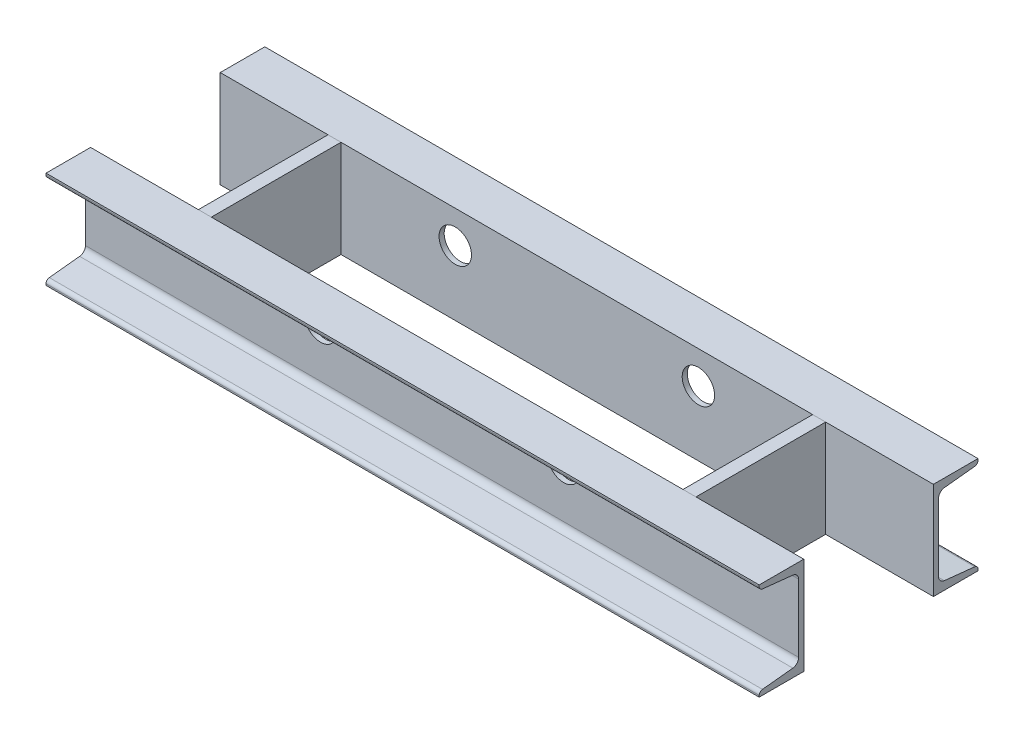
SolidWorks part; units mm, degrees
other "DetailItem17"
other "DetailItem18"
other "DetailItem14"
other "DetailItem15"
other "DetailItem16"
other "DetailItem19"
other "DetailItem20"
other "DetailItem21"
other "Weld Folder"
other "Weld Bead9"
other "Weld Bead10"
other "Weld Bead11"
other "Weld Bead12"
other "Weld Bead13"
other "Weld Bead14"
other "Weld Bead15"
other "Weld Bead16"
ref_plane "Front Plane" through (0, 0, 0) normal (0, 0, 1) x (1, 0, 0)
ref_plane "Top Plane" through (0, 0, 0) normal (0, 1, 0) x (1, 0, 0)
ref_plane "Right Plane" through (0, 0, 0) normal (1, 0, 0) x (0, 0, -1)
sketch "Sketch1" plane through (0, 0, 0) normal (0, 0, 1) x (1, 0, 0)
  line L0 (-440, 0) -> (440, 0)
  dimension "D1" = 440
  dimension "D2" = 880
other "C channel 120 X 12(1)"
ref_plane "Plane1" through (-440, 0, 0) normal (1, 0, 0) x (0, 0, 1)
sketch "Sketch13" plane through (-440, 0, 0) normal (1, 0, 0) x (0, 0, 1)
  line L0 (55, 120) -> (0, 120)
  line L1 (55, 0) -> (0, 0)
  line L2 (0, 120) -> (0, 0)
  line L6 (55, 120) -> (55, 118.1136)
  line L7 (55, 0) -> (55, 1.8964)
  line L12 (6.3, 101.74) -> (6.3, 18.27)
  line L17 (13.4638, 109.6962) -> (50.9704, 113.6383)
  line L18 (13.4638, 10.3138) -> (50.9704, 6.3717)
  arc A0 (50.9704, 113.6383) -> (55, 118.1136) centre (50.5, 118.1136) ccw
  arc A1 (50.9704, 6.3717) -> (55, 1.8964) centre (50.5, 1.8964) cw
  arc A9 (6.3, 18.27) -> (13.4638, 10.3138) centre (14.3, 18.27) ccw
  arc A10 (6.3, 101.74) -> (13.4638, 109.6962) centre (14.3, 101.74) cw
  point P8 (0, 60)
  point P9 (6.3, 60.005)
  point P10 (27.5, 120)
  point P11 (27.5, 0)
  point P12 (55, 5.9482)
  point P13 (55, 114.0618)
  point P14 (0, 0)
  dimension "D4" = 4.5
  dimension "RI" = 8
  dimension "D2" = 6
  dimension "D3" = 18.26
  dimension "Depth" = 120
  dimension "BF" = 55
  dimension "TW" = 6.3
  dimension "d1" = 83.47
ref_plane "Plane2" through (0, 0, -160) normal (0, 0, -1) x (-1, 0, 0)
sketch "Sketch15" plane through (0, 0, -160) normal (0, 0, -1) x (-1, 0, 0)
  line L0 (-440, 0) -> (440, 0)
other "C channel 120 X 12(2)"
ref_plane "Plane3" through (440, 0, -160) normal (-1, 0, 0) x (0, 0, -1)
sketch "Sketch16" plane through (440, 0, -160) normal (-1, 0, 0) x (0, 0, -1)
  line L0 (55, 120) -> (0, 120)
  line L1 (55, 0) -> (0, 0)
  line L2 (0, 120) -> (0, 0)
  line L6 (55, 120) -> (55, 118.1136)
  line L7 (55, 0) -> (55, 1.8964)
  line L12 (6.3, 101.74) -> (6.3, 18.27)
  line L17 (13.4638, 109.6962) -> (50.9704, 113.6383)
  line L18 (13.4638, 10.3138) -> (50.9704, 6.3717)
  arc A0 (50.9704, 113.6383) -> (55, 118.1136) centre (50.5, 118.1136) ccw
  arc A1 (50.9704, 6.3717) -> (55, 1.8964) centre (50.5, 1.8964) cw
  arc A9 (6.3, 18.27) -> (13.4638, 10.3138) centre (14.3, 18.27) ccw
  arc A10 (6.3, 101.74) -> (13.4638, 109.6962) centre (14.3, 101.74) cw
  point P8 (0, 60)
  point P9 (6.3, 60.005)
  point P10 (27.5, 120)
  point P11 (27.5, 0)
  point P12 (55, 5.9482)
  point P13 (55, 114.0618)
  point P14 (0, 0)
  dimension "D4" = 4.5
  dimension "RI" = 8
  dimension "D2" = 6
  dimension "D3" = 18.26
  dimension "Depth" = 120
  dimension "BF" = 55
  dimension "TW" = 6.3
  dimension "d1" = 83.47
sketch "Sketch18" plane through (0, 0, 6.3) normal (0, 0, 1) x (1, 0, 0)
  line L5 (440, 0) -> (-440, 0) construction
  circle A0 centre (-150, -40) radius 20
  circle A1 centre (150, -40) radius 20
  dimension "D1" = 40
  dimension "D2" = 40
  dimension "D3" = 150
  dimension "D4" = 150
  dimension "D5" = 40
  dimension "D6" = 40
extrude "Cut-Extrude3" cut sketch "Sketch18" against normal through all both and the other way through all
sketch "Sketch19" plane through (0, 0, 0) normal (0, 0, -1) x (-1, 0, 0)
  line L0 (440, 0) -> (-440, 0) construction
  line L1 (-307, 0) -> (-291, 0)
  line L2 (-307, 0) -> (-307, -120)
  line L3 (-307, -120) -> (-291, -120)
  line L4 (-291, 0) -> (-291, -120)
  line L5 (-440, -120) -> (440, -120) construction
  line L7 (291, 0) -> (307, 0)
  line L8 (291, 0) -> (291, -120)
  line L9 (291, -120) -> (307, -120)
  line L10 (307, 0) -> (307, -120)
  dimension "D1" = 16
  dimension "D2" = 16
  dimension "D3" = 291
  dimension "D4" = 291
extrude "Boss-Extrude1" add sketch "Sketch19" along normal up to next separate body
